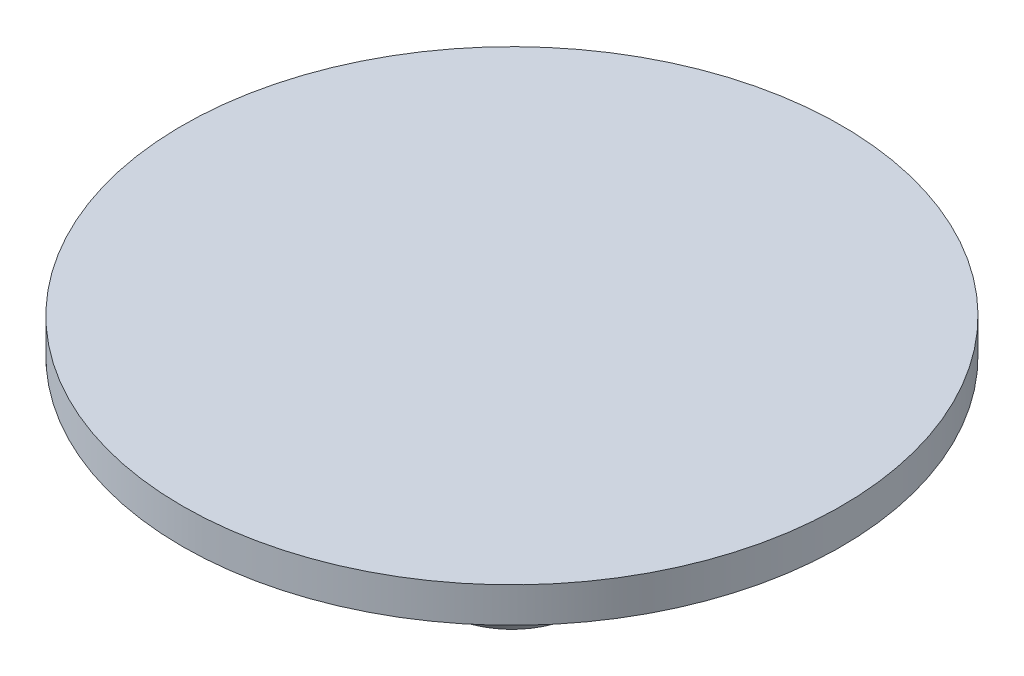
SolidWorks part; units mm, degrees
material "6061 Alloy"
ref_plane "Front Plane" through (0, 0, 0) normal (0, 0, 1) x (1, 0, 0)
ref_plane "Top Plane" through (0, 0, 0) normal (0, 1, 0) x (1, 0, 0)
ref_plane "Right Plane" through (0, 0, 0) normal (1, 0, 0) x (0, 0, -1)
sketch "Sketch1" plane through (0, 0, 0) normal (0, 0, 1) x (1, 0, 0)
  line L0 (0, 0) -> (0, -1.5)
  line L1 (0, -1.5) -> (2, -1.5)
  line L2 (2, -1.5) -> (2, -9.5)
  line L3 (2, -9.5) -> (3, -9.5)
  line L4 (3, -9.5) -> (6.85, -1.5)
  line L5 (6.85, -1.5) -> (14.1, -1.5)
  line L6 (14.1, -1.5) -> (14.1, 0)
  line L7 (14.1, 0) -> (0, 0)
  point P8 (0, 0)
  dimension "D1" = 1.5
  dimension "D2" = 2
  dimension "D3" = 9.5
  dimension "D4" = 3
  dimension "D5" = 14.1
  dimension "D6" = 6.85
revolve "Revolve1" add sketch "Sketch1" angle 360 about L0
sketch "Sketch2" plane through (0, 0, 0) normal (0, 0, 1) x (1, 0, 0)
  line L0 (-6.85, -1.5) -> (6.85, -1.5) construction
  circle A0 centre (0, -5.6) radius 1.25
  point P2 (0, 0)
  dimension "D1" = 2.5
  dimension "D2" = 4.1
extrude "Cut-Extrude1" cut sketch "Sketch2" against normal blind 10
